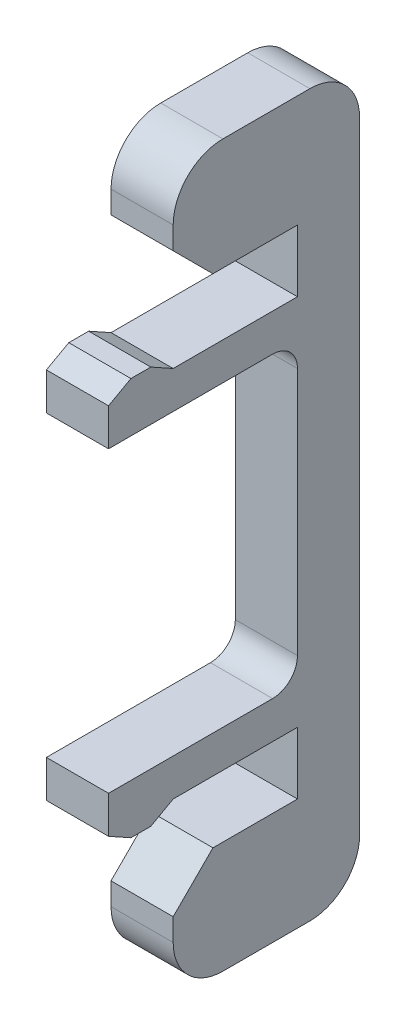
SolidWorks part; units mm, degrees
ref_plane "Front Plane" through (0, 0, 0) normal (0, 0, 1) x (1, 0, 0)
ref_plane "Top Plane" through (0, 0, 0) normal (0, 1, 0) x (1, 0, 0)
ref_plane "Right Plane" through (0, 0, 0) normal (1, 0, 0) x (0, 0, -1)
sketch "Sketch1" plane through (0, 0, 0) normal (0, 0, 1) x (1, 0, 0)
  line L1 (-1.5875, -18.415) -> (1.5875, -18.415)
  line L2 (-1.5875, -18.415) -> (-1.5875, 18.415)
  line L3 (-1.5875, 18.415) -> (1.5875, 18.415)
  line L4 (1.5875, -18.415) -> (1.5875, 18.415)
  line L5 (-1.5875, -18.415) -> (1.5875, 18.415) construction
  line L6 (-1.5875, 18.415) -> (1.5875, -18.415) construction
  point P0 (0, 0)
  dimension "D1" = 36.83
  dimension "D2" = 3.175
extrude "Base" add sketch "Sketch1" along normal blind 3.175
sketch "Sketch3" plane through (-1.5875, 0, 0) normal (-1, 0, 0) x (0, 0, 1)
  line L0 (3.175, 12.7) -> (9.525, 12.7)
  line L1 (3.175, 18.415) -> (3.175, -18.415) construction
  line L3 (3.175, -12.7) -> (9.525, -12.7)
  line L5 (3.175, 18.415) -> (3.175, 12.7)
  line L6 (3.175, -12.7) -> (3.175, -18.415)
  line L7 (3.175, 18.415) -> (9.525, 18.415)
  line L9 (3.175, -18.415) -> (9.525, -18.415)
  line L10 (9.525, -18.415) -> (9.525, -12.7)
  line L11 (9.525, 18.415) -> (9.525, 12.7)
  dimension "D1" = 6.35
  dimension "D2" = 25.4
extrude "Retainer" add sketch "Sketch3" against normal up to surface (3.175 mm away) up to face at (1.5875, 0, 1.5875)
sketch "Sketch5" plane through (-1.5875, 0, 0) normal (-1, 0, 0) x (0, 0, 1)
  line L0 (3.175, 9.525) -> (9.525, 9.525)
  line L1 (3.175, 12.7) -> (3.175, -12.7) construction
  line L2 (9.525, 9.525) -> (10.668, 10.16)
  line L3 (10.668, 10.16) -> (11.684, 10.16)
  line L4 (11.684, 10.16) -> (12.827, 9.525)
  line L5 (12.827, 9.525) -> (12.827, 7.62)
  line L6 (12.827, 7.62) -> (3.175, 7.62)
  line L7 (3.175, 9.525) -> (12.827, 9.525) construction
  line L8 (3.175, 12.7) -> (9.525, 12.7) construction
  line L9 (3.175, 0) -> (18.8887, 0) construction
  line L10 (3.175, -9.525) -> (12.827, -9.525) construction
  line L11 (12.827, -7.62) -> (3.175, -7.62)
  line L12 (12.827, -9.525) -> (12.827, -7.62)
  line L13 (11.684, -10.16) -> (12.827, -9.525)
  line L14 (10.668, -10.16) -> (11.684, -10.16)
  line L15 (9.525, -9.525) -> (10.668, -10.16)
  line L16 (3.175, -9.525) -> (9.525, -9.525)
  line L17 (3.175, 9.525) -> (3.175, 7.62)
  line L18 (3.175, -7.62) -> (3.175, -9.525)
  dimension "D1" = 6.35
  dimension "D2" = 1.905
  dimension "D3" = 1.016
  dimension "D4" = 9.652
  dimension "D5" = 0.635
  dimension "D6" = 3.175
extrude "Tab" add sketch "Sketch5" against normal up to surface (3.175 mm away) up to face at (1.5875, 0, 5.5562)
fillet "Fillet1" radius 1.27 2 edges at (0, -7.62, 3.175) (0, 7.62, 3.175)
fillet "Fillet2" radius 2.54 4 edges at (0, 18.415, 0) (0, -18.415, 0) (0, -18.415, 9.525) (0, 18.415, 9.525)
chamfer "Chamfer1" distance 2.032 angle 45 2 edges at (0, -12.7, 9.525) (0, 12.7, 9.525)
